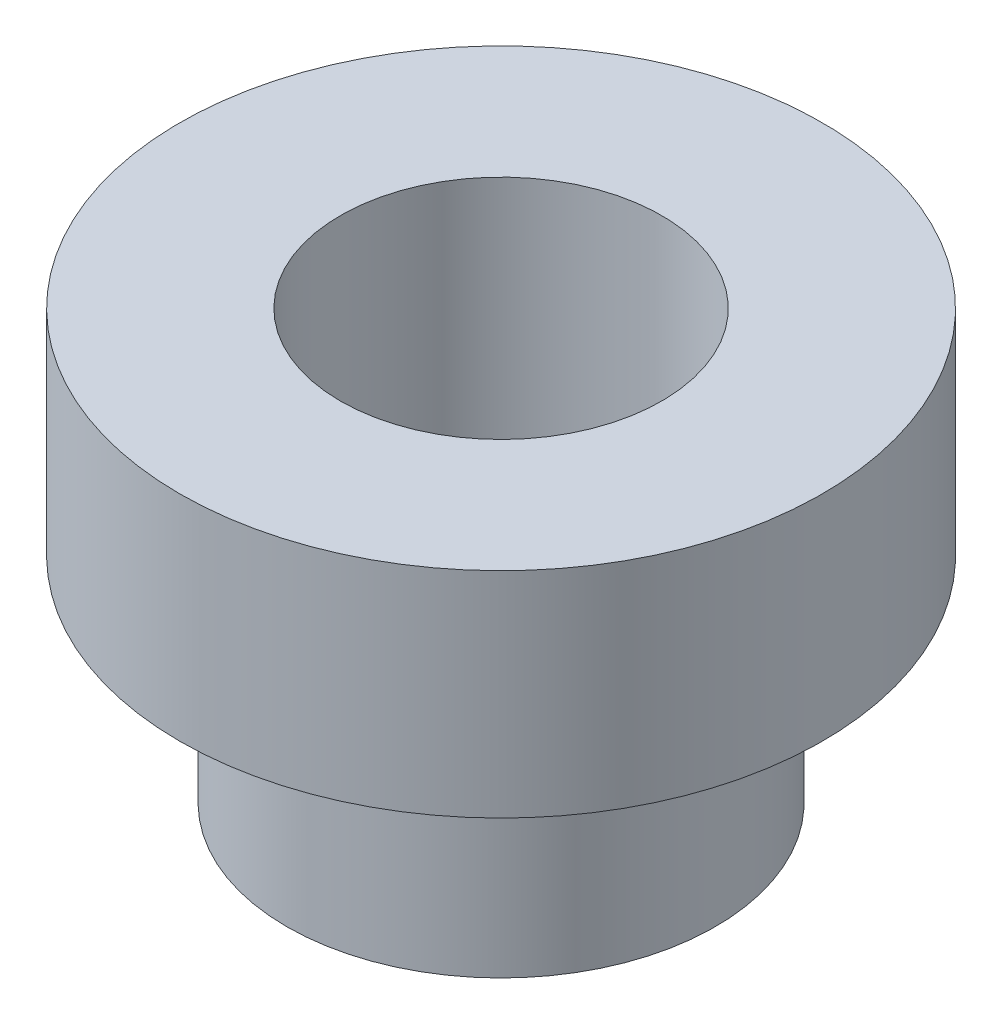
SolidWorks part; units mm, degrees
ref_plane "Front Plane" through (0, 0, 0) normal (0, 0, 1) x (1, 0, 0)
ref_plane "Top Plane" through (0, 0, 0) normal (0, 1, 0) x (1, 0, 0)
ref_plane "Right Plane" through (0, 0, 0) normal (1, 0, 0) x (0, 0, -1)
sketch "Sketch2" plane through (0, 0, 0) normal (0, 1, 0) x (1, 0, 0)
  circle A0 centre (0, 0) radius 1.5
  circle A1 centre (0, 0) radius 2
extrude "Boss-Extrude1" add sketch "Sketch2" along normal blind 2
sketch "Sketch3" plane through (0, 2, 0) normal (0, 1, 0) x (1, 0, 0)
  circle A0 centre (0, 0) radius 1.5
  circle A1 centre (0, 0) radius 3
extrude "Boss-Extrude2" add sketch "Sketch3" along normal blind 2
